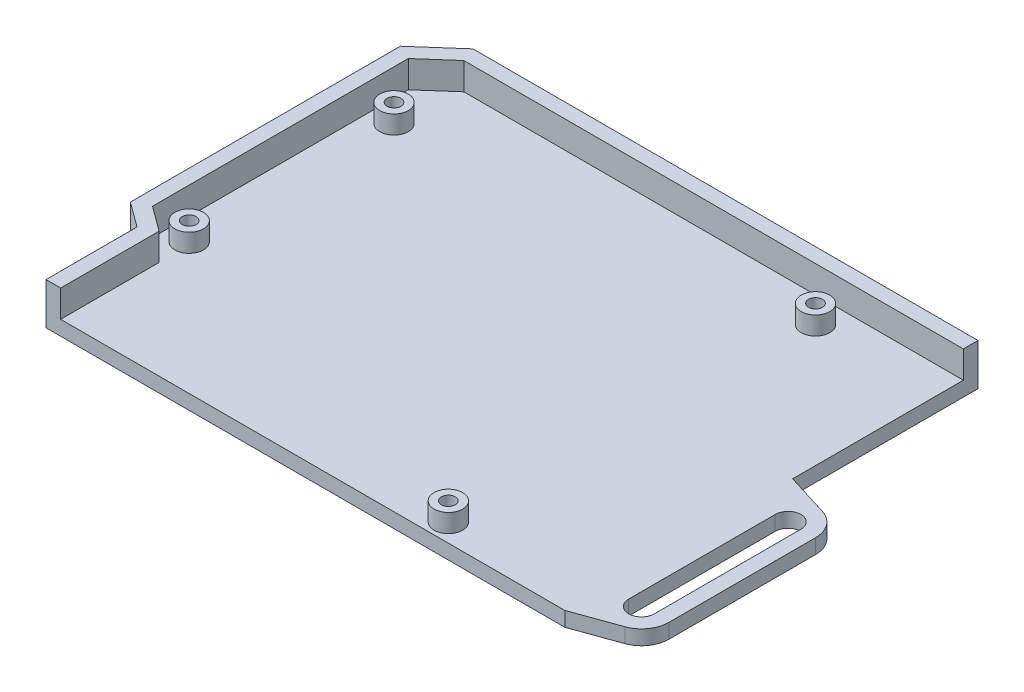
SolidWorks part; units mm, degrees
ref_plane "Alzado" through (0, 0, 0) normal (0, 0, 1) x (1, 0, 0)
ref_plane "Planta" through (0, 0, 0) normal (0, 1, 0) x (1, 0, 0)
ref_plane "Vista lateral" through (0, 0, 0) normal (1, 0, 0) x (0, 0, -1)
sketch "Croquis1" plane through (0, 0, 0) normal (0, 1, 0) x (1, 0, 0)
  point P0 (0, 0)
  line B0 (67.7991, 53.4) -> (3, 53.4)
  line B1 (3, 53.4) -> (-0.4009, 50.4)
  line B2 (-0.4009, 50.4) -> (-0.4009, 16.44)
  line B3 (-0.4009, 16.44) -> (3, 13.94)
  line B4 (3, 13.94) -> (3, 0)
  line B5 (3, 0) -> (67.7991, 0)
  line B6 (67.7991, 0) -> (67.7991, 53.4)
  line B7 (67.7991, 0) -> (70.7991, 0)
  line B8 (70.7991, 56.4) -> (1.8659, 56.4)
  line B9 (1.8659, 56.4) -> (-3.4009, 51.7541)
  line B10 (-3.4009, 51.7541) -> (-3.4009, 14.9219)
  line B11 (-3.4009, 14.9219) -> (0, 12.4219)
  line B12 (0, 12.4219) -> (0, 0)
  line B13 (70.7991, 0) -> (70.7991, 56.4)
  line B14 (79.3245, 25.7) -> (79.3245, 5.7)
  line B15 (71.8245, 25.7) -> (71.8245, 5.7)
  line B16 (70.7991, 0) -> (76.8423, 2.1708)
  line B17 (70.7991, 31.0926) -> (76.6772, 29.2842)
  line B18 (0, 0) -> (3, 0)
  line B19 (68.7991, 54.4) -> (2.622, 54.4)
  line B20 (2.622, 54.4) -> (-1.4009, 50.8514)
  line B21 (-1.4009, 50.8514) -> (-1.4009, 15.934)
  line B22 (-1.4009, 15.934) -> (2, 13.434)
  line B23 (2, 13.434) -> (2, -1)
  line B24 (2, -1) -> (68.7991, -1)
  line B25 (68.7991, -1) -> (68.7991, 54.4)
  arc B26 (71.8245, 5.7) -> (79.3245, 5.7) centre (75.5745, 5.7) ccw
  arc B27 (79.3245, 25.7) -> (71.8245, 25.7) centre (75.5745, 25.7) ccw
  circle B28 centre (1.5991, 17.94) radius 0.95
  circle B29 centre (1.5991, 45.9) radius 0.95
  circle B30 centre (54.1191, 50.9) radius 0.95
  circle B31 centre (52.4091, 2.505) radius 0.95
  line B32 (75.5745, 25.7) -> (75.5745, 5.7) construction
  line B33 (77.3245, 25.7) -> (77.3245, 5.7)
  line B34 (73.8245, 25.7) -> (73.8245, 5.7)
  arc B35 (77.3245, 25.7) -> (73.8245, 25.7) centre (75.5745, 25.7) ccw
  arc B36 (73.8245, 5.7) -> (77.3245, 5.7) centre (75.5745, 5.7) ccw
sketch_block_instance "Bloque2-1"
sketch_block "Bloque2"
extrude "Saliente-Extruir2" add sketch "Croquis1" along normal blind 2 contours B5 B6 B0 B1 B2 B3 B4 B31 B30 B29 B28 | B25 B7 B13 B8 B9 B10 B11 B12 B18 B23 B22 B21 B20 B19 | B7 B25 B19 B20 B21 B22 B23 B18 B4 B3 B2 B1 B0 B6 | B27 B17 B13 B16 B26 B15 | B14 B27 B15 B26 B36 B34 B35 B33
sketch "Croquis2" plane through (0, 2, 0) normal (0, 1, 0) x (1, 0, 0)
  line L10 (70.7991, 31.0926) -> (70.7991, 56.4) construction
  line L11 (0, 0) -> (70.7991, 0) construction
  line L12 (70.7991, 56.4) -> (1.8659, 56.4) construction
  line L13 (1.8659, 56.4) -> (-3.4009, 51.7541) construction
  line L14 (-3.4009, 51.7541) -> (-3.4009, 14.9219) construction
  line L15 (-3.4009, 14.9219) -> (0, 12.4219) construction
  line L16 (0, 12.4219) -> (0, 0) construction
  line L34 (70.7991, 54.4) -> (2.622, 54.4)
  line L35 (2.622, 54.4) -> (-1.4009, 50.8514)
  line L36 (-1.4009, 50.8514) -> (-1.4009, 15.934)
  line L37 (-1.4009, 15.934) -> (2, 13.434)
  line L38 (2, 13.434) -> (2, 0)
  line L40 (70.7991, 0) -> (76.8423, 2.1708)
  line L41 (79.3245, 5.7) -> (79.3245, 25.7)
  line L42 (76.6772, 29.2842) -> (70.7991, 31.0926)
  line L43 (70.7991, 31.0926) -> (70.7991, 56.4)
  line L44 (70.7991, 56.4) -> (1.8659, 56.4)
  line L45 (1.8659, 56.4) -> (-3.4009, 51.7541)
  line L46 (-3.4009, 51.7541) -> (-3.4009, 14.9219)
  line L47 (-3.4009, 14.9219) -> (0, 12.4219)
  line L48 (0, 12.4219) -> (0, 0)
  line L49 (0, 0) -> (70.7991, 0)
  line L53 (70.7991, 54.4) -> (70.7991, 56.4)
  line L54 (70.7991, 56.4) -> (1.8659, 56.4)
  line L55 (1.8659, 56.4) -> (-3.4009, 51.7541)
  line L56 (-3.4009, 51.7541) -> (-3.4009, 14.9219)
  line L57 (-3.4009, 14.9219) -> (0, 12.4219)
  line L58 (0, 12.4219) -> (0, 0)
  line L59 (0, 0) -> (2, 0)
  arc A5 (76.8423, 2.1708) -> (79.3245, 5.7) centre (75.5745, 5.7) ccw
  arc A8 (79.3245, 25.7) -> (76.6772, 29.2842) centre (75.5745, 25.7) ccw
  point P0 (2, 0)
  dimension "D1" = 2
  dimension "D2" = 2
  dimension "D3" = 2
  dimension "D4" = 2
  dimension "D5" = 2
  dimension "D6" = 0
extrude "Saliente-Extruir3" add sketch "Croquis2" along normal blind 3.7
sketch "Croquis3" plane through (0, 2, 0) normal (0, 1, 0) x (1, 0, 0)
  circle A0 centre (54.1191, 50.9) radius 0.95 construction
  circle A1 centre (52.4091, 2.505) radius 0.95 construction
  circle A2 centre (1.5991, 17.94) radius 0.95 construction
  circle A3 centre (1.5991, 45.9) radius 0.95 construction
  circle A4 centre (54.1191, 50.9) radius 0.95
  circle A5 centre (52.4091, 2.505) radius 0.95
  circle A6 centre (1.5991, 17.94) radius 0.95
  circle A7 centre (1.5991, 45.9) radius 0.95
  circle A8 centre (1.5991, 45.9) radius 1.95
  circle A9 centre (1.5991, 17.94) radius 1.95
  circle A10 centre (52.4091, 2.505) radius 1.95
  circle A11 centre (54.1191, 50.9) radius 1.95
  dimension "D1" = 1
extrude "Saliente-Extruir4" add sketch "Croquis3" along normal blind 2.5
